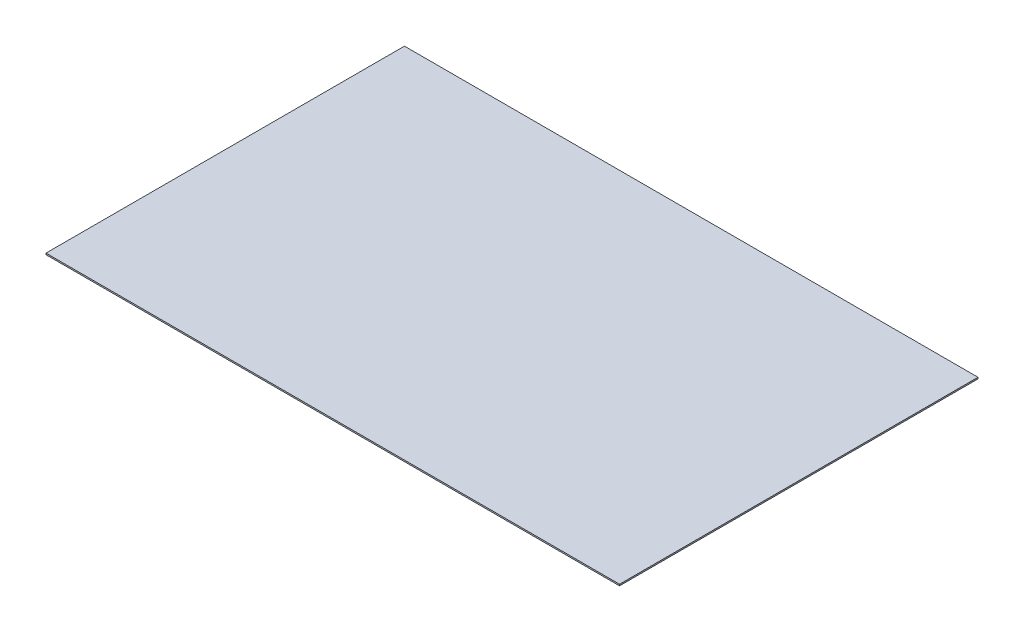
SolidWorks part; units mm, degrees
ref_plane "前基準面" through (0, 0, 0) normal (0, 0, 1) x (1, 0, 0)
ref_plane "上基準面" through (0, 0, 0) normal (0, 1, 0) x (1, 0, 0)
ref_plane "右基準面" through (0, 0, 0) normal (1, 0, 0) x (0, 0, -1)
sketch "草圖1" plane through (0, 0, 0) normal (0, 1, 0) x (1, 0, 0)
  line L1 (-2000, -1250) -> (2000, -1250)
  line L2 (-2000, -1250) -> (-2000, 1250)
  line L3 (-2000, 1250) -> (2000, 1250)
  line L4 (2000, -1250) -> (2000, 1250)
  line L5 (-2000, -1250) -> (2000, 1250) construction
  line L6 (-2000, 1250) -> (2000, -1250) construction
  point P0 (0, 0)
  dimension "D1" = 4000
  dimension "D2" = 2500
extrude "填料-伸長1" add sketch "草圖1" along normal blind 10
